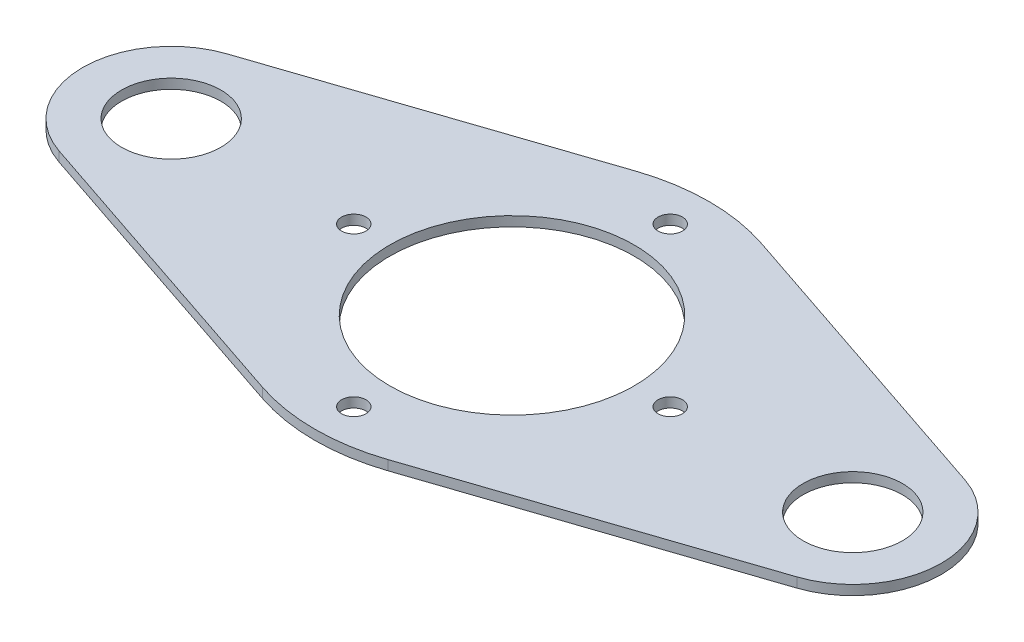
SolidWorks part; units mm, degrees
ref_plane "Front Plane" through (0, 0, 0) normal (0, 0, 1) x (1, 0, 0)
ref_plane "Top Plane" through (0, 0, 0) normal (0, 1, 0) x (1, 0, 0)
ref_plane "Right Plane" through (0, 0, 0) normal (1, 0, 0) x (0, 0, -1)
sketch "Sketch1" plane through (0, 0, 0) normal (0, 1, 0) x (1, 0, 0)
  line L0 (0, 0) -> (88.9, 0) construction
  line L1 (16.3857, 48.7552) -> (96.2635, 21.9097)
  line L2 (16.3857, -48.7552) -> (96.2635, -21.9097)
  line L3 (0, 41.275) -> (0, -41.275) construction
  line L4 (-16.3857, -48.7552) -> (-96.2635, -21.9097)
  line L5 (-16.3857, 48.7552) -> (-96.2635, 21.9097)
  circle A0 centre (0, 0) radius 41.275 construction
  circle A1 centre (0, 0) radius 31.877
  circle A2 centre (88.9, 0) radius 12.954
  arc A3 (-16.3857, -48.7552) -> (51.435, 0) centre (0, 0) ccw
  arc A4 (96.2635, -21.9097) -> (96.2635, 21.9097) centre (88.9, 0) ccw
  circle A5 centre (0, 41.275) radius 3.175
  circle A6 centre (41.275, 0) radius 3.175
  circle A7 centre (0, -41.275) radius 3.175
  circle A8 centre (-41.275, 0) radius 3.175
  arc A9 (-96.2635, -21.9097) -> (-96.2635, 21.9097) centre (-88.9, 0) cw
  circle A10 centre (-88.9, 0) radius 12.954
  circle A11 centre (88.9, 0) radius 23.114 construction
  circle A12 centre (0, 0) radius 51.435 construction
  arc A13 (16.3857, 48.7552) -> (-16.3857, 48.7552) centre (0, 0) ccw
  point P21 (0, 0)
  dimension "D1" = 82.55
  dimension "D2" = 63.754
  dimension "D3" = 25.908
  dimension "D6" = 6.35
  dimension "D4" = 88.9
  dimension "D5" = 10.16
  dimension "D7" = 4
extrude "Boss-Extrude1" add sketch "Sketch1" along normal blind 2.54
